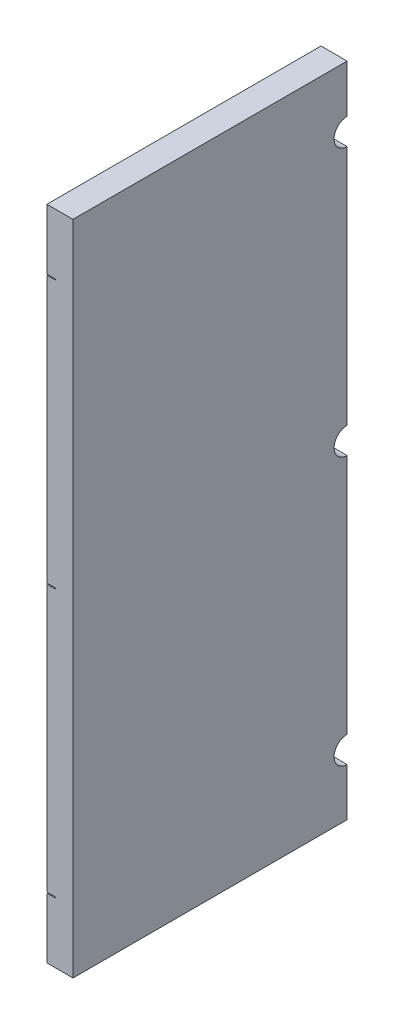
SolidWorks part; units mm, degrees
ref_plane "Спереди" through (0, 0, 0) normal (0, 0, 1) x (1, 0, 0)
ref_plane "Сверху" through (0, 0, 0) normal (0, 1, 0) x (1, 0, 0)
ref_plane "Справа" through (0, 0, 0) normal (1, 0, 0) x (0, 0, -1)
other "Configuration Table"
sketch "Эскиз1" plane through (0, 0, 0) normal (0, 0, 1) x (1, 0, 0)
  line L1 (0, 0) -> (3, 0)
  line L2 (0, 0) -> (0, 74)
  line L3 (0, 74) -> (3, 74)
  line L4 (3, 0) -> (3, 74)
extrude "Бобышка-Вытянуть1" add sketch "Эскиз1" along normal blind 31.5
sketch "Эскиз2" plane through (0, 0, 0) normal (0, 0, 1) x (1, 0, 0)
  line L1 (0, 74) -> (3, 74)
  line L2 (0, 74) -> (0, 75.5)
  line L3 (0, 75.5) -> (3, 75.5)
  line L4 (3, 74) -> (3, 75.5)
extrude "side_rear_extension_1p5mm" add sketch "Эскиз2" along normal blind 31.5
sketch "Эскиз3" plane through (0, 0, 0) normal (-1, 0, 0) x (0, 0, 1)
  circle A0 centre (30.001, 7) radius 1.5
  circle A1 centre (30.001, 37.75) radius 1.5
  circle A2 centre (30.001, 68.5) radius 1.5
extrude "side_top_edge_magnet_pockets_D3_depth1_3x" cut sketch "Эскиз3" against normal blind 1
sketch "Эскиз4" plane through (0, 0, 0) normal (-1, 0, 0) x (0, 0, 1)
  line L0 (0, 5.5) -> (0, 8.5)
  line L1 (0, 36.25) -> (0, 39.25)
  line L2 (0, 67) -> (0, 70)
  arc A0 (0, 5.5) -> (0, 8.5) centre (0, 7) ccw
  arc A1 (0, 36.25) -> (0, 39.25) centre (0, 37.75) ccw
  arc A2 (0, 67) -> (0, 70) centre (0, 68.5) ccw
extrude "side_bottom_edge_semicircles_D3_through_3x" cut sketch "Эскиз4" against normal blind 4
